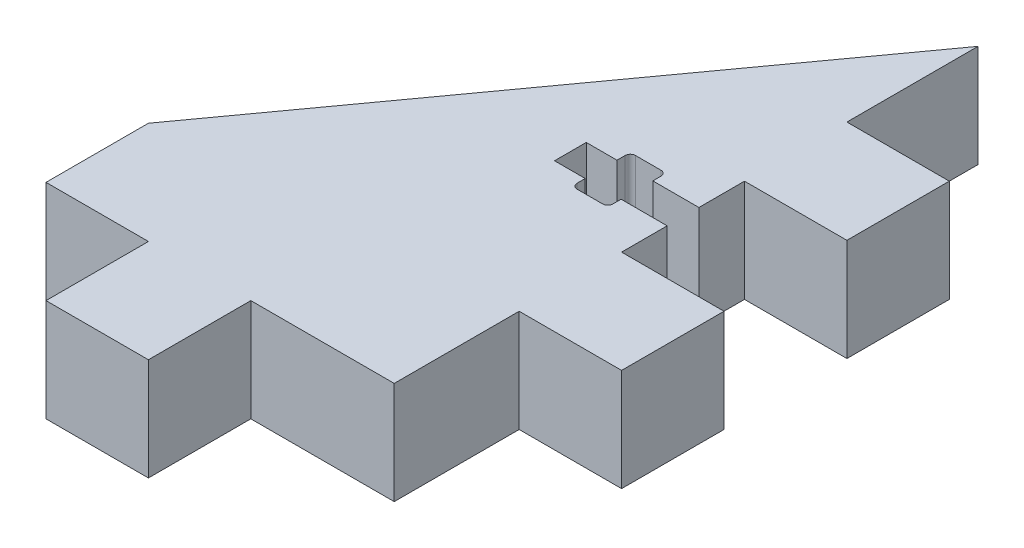
SolidWorks part; units mm, degrees
ref_plane "Front Plane" through (0, 0, 0) normal (0, 0, 1) x (1, 0, 0)
ref_plane "Top Plane" through (0, 0, 0) normal (0, 1, 0) x (1, 0, 0)
ref_plane "Right Plane" through (0, 0, 0) normal (1, 0, 0) x (0, 0, -1)
sketch "Sketch1" plane through (0, 0, 0) normal (0, 1, 0) x (1, 0, 0)
  line L0 (0, 0) -> (-14, 0)
  line L1 (-14, 0) -> (-14, -10)
  line L2 (-14, -10) -> (-24, -10)
  line L3 (-24, -10) -> (-24, 0)
  line L4 (-24, 0) -> (-34, 0)
  line L5 (-34, 0) -> (-34, 10)
  line L6 (-34, 10) -> (0, 57)
  line L7 (0, 57) -> (0, 44.2)
  line L8 (0, 44.2) -> (10, 44.2)
  line L9 (10, 44.2) -> (10, 34.2)
  line L10 (10, 34.2) -> (0, 34.2)
  line L11 (0, 34.2) -> (0, 22.2)
  line L12 (-24, 0) -> (-14, 0) construction
  line L13 (-19, 0) -> (-19, -10) construction
  line L14 (0, 17.2) -> (0, 12.2) construction
  line L15 (5, 12.2) -> (5, 21.2) construction
  line L16 (10, 34.2) -> (10, 22.2) construction
  line L17 (0, 28.2) -> (10, 28.2) construction
  line L24 (0, 22.2) -> (10, 22.2)
  line L25 (10, 22.2) -> (10, 12.2)
  line L26 (10, 12.2) -> (0, 12.2)
  line L27 (0, 12.2) -> (0, 0)
  line L32 (10, 39.2) -> (0, 39.2) construction
  line L33 (0, 39.2) -> (0, 34.2) construction
  line L34 (10, 17.2) -> (0, 17.2) construction
  line L35 (0, 17.2) -> (0, 22.2) construction
  dimension "D1" = 10
  dimension "D2" = 10
  dimension "D3" = 10
  dimension "D7" = 10
  dimension "D8" = 10
  dimension "D10" = 10
  dimension "D11" = 10
  dimension "D12" = 10
  dimension "D9" = 57
  dimension "D4" = 22
  dimension "D6" = 24
  dimension "D5" = 28.2
extrude "Boss-Extrude1" add sketch "Sketch1" along normal blind 10
sketch "Sketch2" [suppressed] plane through (0, 8, 0) normal (0, 1, 0) x (1, 0, 0)
  line L0 (0, 29.9) -> (0, 25.9) construction
  line L1 (0, 27.9) -> (-7.2, 27.9) construction
  line L2 (-7.2, 25.9) -> (-7.2, 29.9) construction
  line L3 (7.5, 36.4) -> (7.5, 20.4) construction
  line L4 (0, 36.4) -> (7.5, 36.4) construction
  line L5 (0, 27.9) -> (7.5, 27.9) construction
sketch "Sketch3" plane through (0, 10, 0) normal (0, 1, 0) x (1, 0, 0)
  line L0 (0, 28.2) -> (-11, 28.2) construction
  line L1 (0, 22.2) -> (0, 34.2) construction
  line L2 (-11, 29.75) -> (-8, 29.75)
  line L3 (-8, 29.75) -> (-8, 30.55)
  line L4 (-7.5, 31.05) -> (-5, 31.05)
  line L5 (-4.5, 30.55) -> (-4.5, 29.75)
  line L6 (-4.5, 29.75) -> (0, 29.75)
  line L7 (0, 29.75) -> (0, 26.65)
  line L8 (-11, 29.75) -> (-11, 26.65)
  line L9 (-4.5, 26.65) -> (0, 26.65)
  line L10 (-4.5, 25.85) -> (-4.5, 26.65)
  line L11 (-7.5, 25.35) -> (-5, 25.35)
  line L12 (-8, 26.65) -> (-8, 25.85)
  line L13 (-11, 26.65) -> (-8, 26.65)
  arc A0 (-8, 30.55) -> (-7.5, 31.05) centre (-7.5, 30.55) cw
  arc A1 (-5, 31.05) -> (-4.5, 30.55) centre (-5, 30.55) cw
  arc A2 (-5, 25.35) -> (-4.5, 25.85) centre (-5, 25.85) ccw
  arc A3 (-8, 25.85) -> (-7.5, 25.35) centre (-7.5, 25.85) ccw
  point P12 (-8, 31.05)
  point P15 (-4.5, 31.05)
  point P26 (-4.5, 25.35)
  point P27 (-8, 25.35)
  dimension "D7" = 0.5
  dimension "D1" = 11
  dimension "D3" = 1.55
  dimension "D2" = 8
  dimension "D4" = 3.5
  dimension "D5" = 2.85
  dimension "D6" = 1.55
extrude "Cut-Extrude1" cut sketch "Sketch3" against normal through all
equation "\"Y-ROD-SPACING\"=75"
equation "\"Y-BED-OFFSET\"=2"
equation "\"Y-BED-ROD-INSET\"=3.5"
equation "\"T-SLOT-NUT-FILLET-RADIUS\"=0.5"
equation "\"T-SLOT-SCREW-SHAFT-RADIUS\"=1.55"
equation "\"T-SLOT-SCREW-SHAFT-CUTOUT-LENGTH\"=11"
equation "\"T-SLOT-NUT-DEPTH\"=3.5"
equation "\"T-SLOT-NUT-WIDTH\"=2.85"
equation "\"T-SLOT-NUT-END-DISTANCE\"=8"
equation "\"ACRYLIC-TAB-CUTOUT-SIZE\"=\"ACRYLIC-THICKNESS\"+\"ACRYLIC-TAB-TOLERANCE\"*2"
equation "\"ACRYLIC-TAB-WIDTH\"=\"ACRYLIC-THICKNESS\""
equation "\"ACRYLIC-M3-HOLE\"=2.9"
equation "\"SMOOTHROD-CAP-SCREW-DISTANCE\"=20"
equation "\"FRAME-WIDTH-INNER\"=370"
equation "\"NEMA17-HOLE-SPACING\"=31"
equation "\"NEMA17-CENTRAL-CUTOUT\"=22.5"
equation "\"D3@Sketch1\"=\"ACRYLIC-TAB-WIDTH\""
equation "\"D12@Sketch1\"=\"ACRYLIC-TAB-WIDTH\""
equation "\"D2@Sketch1\"=\"ACRYLIC-TAB-WIDTH\""
equation "\"D11@Sketch1\"=\"ACRYLIC-TAB-WIDTH\""
equation "\"D1@Sketch1\"=\"ACRYLIC-TAB-WIDTH\""
equation "\"D10@Sketch1\"=\"ACRYLIC-TAB-WIDTH\""
equation "\"Z-BRACKET-REACH\"=57"
equation "\"D9@Sketch1\"=\"Z-BRACKET-REACH\""
equation "\"D6@Sketch3\"=\"T-SLOT-SCREW-SHAFT-RADIUS\""
equation "\"D3@Sketch3\"=\"T-SLOT-SCREW-SHAFT-RADIUS\""
equation "\"D4@Sketch3\"=\"T-SLOT-NUT-DEPTH\""
equation "\"D7@Sketch3\"=\"T-SLOT-NUT-FILLET-RADIUS\""
equation "\"D1@Sketch3\"=\"T-SLOT-SCREW-SHAFT-CUTOUT-LENGTH\""
equation "\"D5@Sketch3\"=\"T-SLOT-NUT-WIDTH\""
equation "\"D2@Sketch3\"=\"T-SLOT-NUT-END-DISTANCE\""
equation "\"X-ROD-SPACING\"=45"
equation "\"Z-ROD-SPACING\"=17.5"
equation "\"ACRYLIC-THICKNESS\"=10"
equation "\"ACRYLIC-THICKNESS2\"=4.5"
equation "\"TOP-BRACKET-SPACING\"=40"
equation "\"SMOOTHROD-X-LENGTH\"=350"
equation "\"SMOOTHROD-Y-LENGTH\"=350"
equation "\"SMOOTHROD-Z-LENGTH\"=350"
equation "\"SMOOTHROD-TIGHTENING-HEADROOM\"=.25"
equation "\"LEADSCREW-Z-LENGTH\"=300"
equation "\"SCREW-LENGTH-FRAME\"=\"ACRYLIC-THICKNESS\" + 10"
equation "\"SCREW-HEAD-RADIUS\"=6"
equation "\"PRINTED-X-SMOOTHROD-DIAMETER\"=8.8"
equation "\"PRINTED-X-SMOOTHROD-CUTOUT\"=10"
equation "\"PRINTED-X-BASE-HEIGHT\"=10"
equation "\"PRINTED-LM8UU-CUTOUT-SIZE\"=15.5"
equation "\"PRINTED-LM8UU-CUTOUT-LENGTH\"=24.5"
equation "\"PRINTED-X-IDLER-HEIGHT\"=16"
equation "\"PSU-MOUNTING-WIDTH\"=95"
equation "\"PSU-MOUNTING-HEIGHT\"=177"
equation "\"D1@Boss-Extrude1\"=\"ACRYLIC-THICKNESS\""
